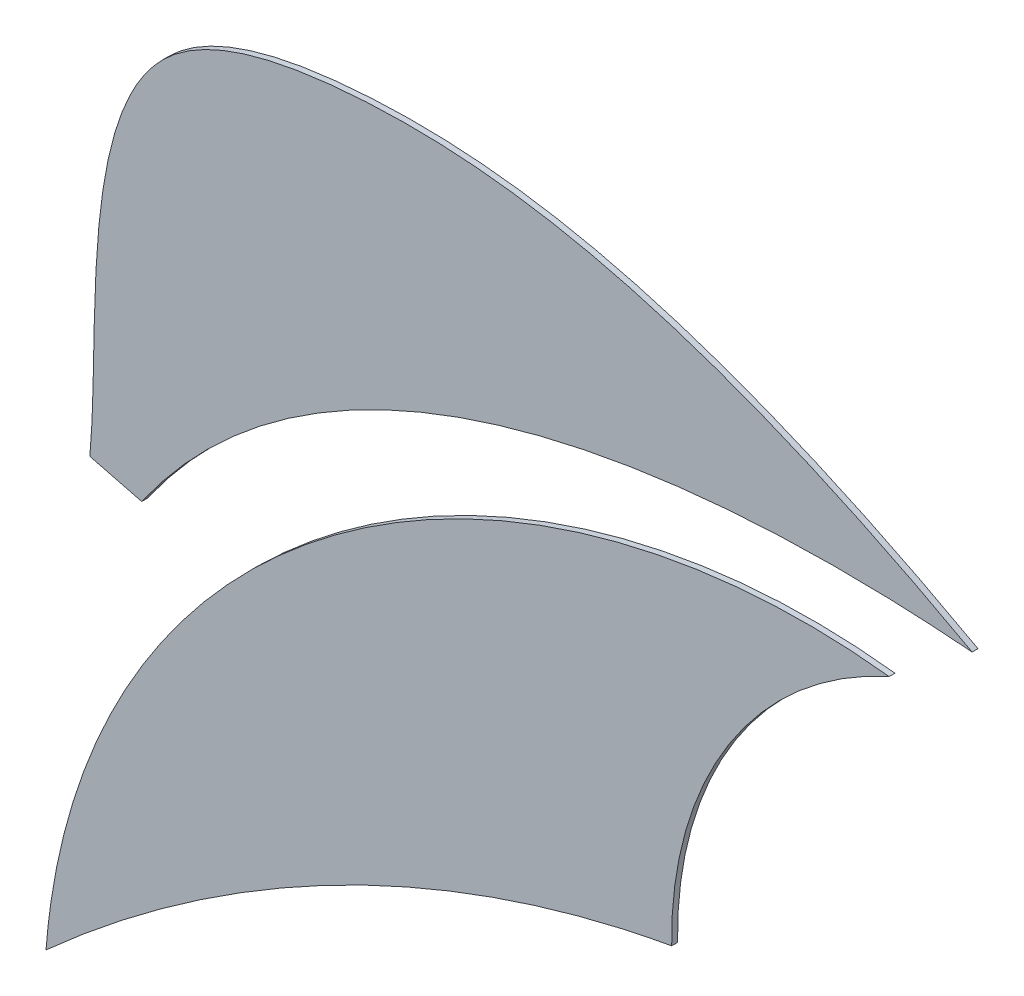
SolidWorks part; units mm, degrees
ref_plane "前视基准面" through (0, 0, 0) normal (0, 0, 1) x (1, 0, 0)
ref_plane "上视基准面" through (0, 0, 0) normal (0, 1, 0) x (1, 0, 0)
ref_plane "右视基准面" through (0, 0, 0) normal (1, 0, 0) x (0, 0, -1)
other "Configuration Table"
sketch "草图1" plane through (0, 0, 0) normal (0, 0, 1) x (1, 0, 0)
  line L0 (16.1551, 56.8469) -> (21.453, 55.5037) construction
  line L1 (16.1551, 56.8469) -> (21.453, 55.5037)
  arc A0 (97.7864, 78.1874) -> (75.579, 43.2682) centre (113.1802, 43.8763) ccw construction
  arc A1 (97.7864, 78.1874) -> (75.579, 43.2682) centre (113.1802, 43.8763) ccw
  spline S0 degree 3 poles (-1582.6059, -2350.1812) (2695.4407, 1940.3366) (-3015.9874, -959.4967) (2971.7271, -32.5753) knots -3.632877 -3.632877 -3.632877 -3.632877 4.389481 4.389481 4.389481 4.389481 only from (97.7864, 78.1874) to (11.6781, 10.9572) construction
  spline S1 degree 3 poles (2644.0835, 1317.1473) (-2377.678, -2522.2355) (1546.0161, 3030.797) (-181.9537, -2887.7829) knots -9.451453 -9.451453 -9.451453 -9.451453 8.814255 8.814255 8.814255 8.814255 only from (11.6781, 10.9572) to (75.579, 43.2682) construction
  spline S2 degree 3 poles (2041.2204, -2137.5815) (-2701.8979, 1984.3945) (3189.8727, -1450.5927) (-2670.8445, 1214.1426) knots -3.914054 -3.914054 -3.914054 -3.914054 5.870191 5.870191 5.870191 5.870191 only from (21.453, 55.5037) to (106.2621, 84.595) construction
  spline S3 degree 3 poles (-1071.2625, 2843.0099) (353.3702, -403.2985) (226.5935, 83.7271) (45.7325, 103.6062) (-56.0671, 83.6991) (292.4364, -359.3447) (-1757.204, 2476.0683) knots -3.713283 -3.713283 -3.713283 -3.713283 0.3174 0.524814 0.681365 2.481153 2.481153 2.481153 2.481153 only from (106.2621, 84.595) to (16.1551, 56.8469) construction
  spline S4 degree 3 poles (97.7864, 78.1874) (57.6902, 82.8687) (14.985, 53.3459) (11.6781, 10.9572) knots 0 0 0 0 1 1 1 1
  spline S5 degree 3 poles (11.6781, 10.9572) (29.6038, 27.0755) (51.7025, 38.987) (75.579, 43.2682) knots 0 0 0 0 1 1 1 1
  spline S6 degree 3 poles (21.453, 55.5037) (40.1498, 82.2123) (76.3866, 87.0493) (106.2621, 84.595) knots 0 0 0 0 1 1 1 1
  spline S7 degree 3 poles (106.2621, 84.595) (94.6421, 90.9758) (73.774, 100.5241) (45.7325, 103.6062) (13.6178, 97.3261) (17.2527, 67.8774) (16.1551, 56.8469) knots 0 0 0 0 0.3174 0.524814 0.681365 1 1 1 1
extrude "凸台-拉伸1" add sketch "草图1" along normal blind 0.6
